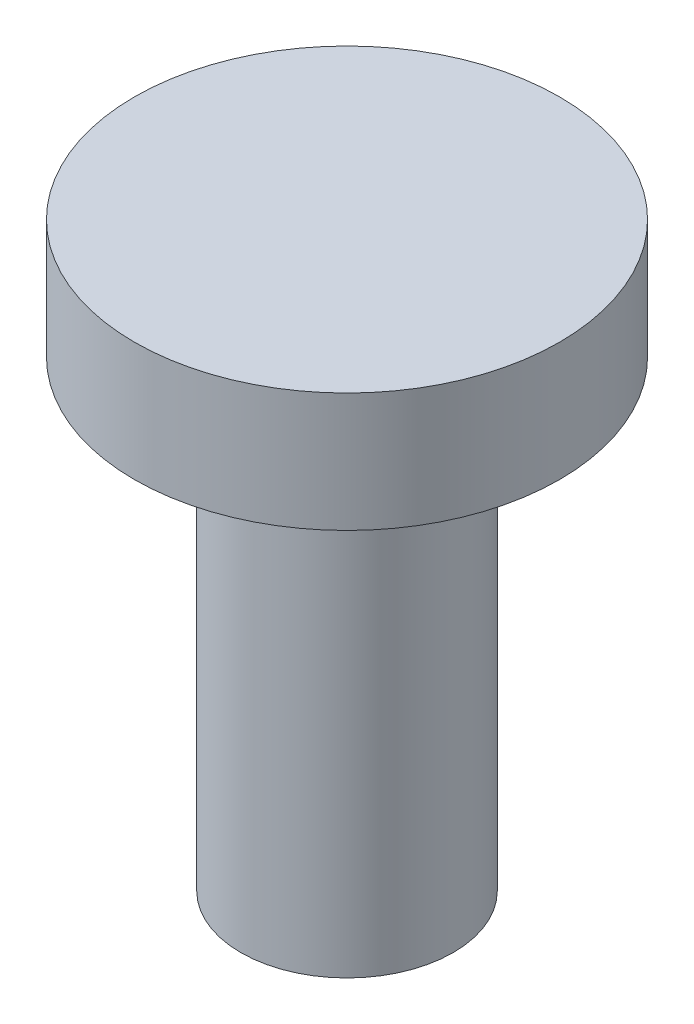
SolidWorks part; units mm, degrees
ref_plane "Front Plane" through (0, 0, 0) normal (0, 0, 1) x (1, 0, 0)
ref_plane "Top Plane" through (0, 0, 0) normal (0, 1, 0) x (1, 0, 0)
ref_plane "Right Plane" through (0, 0, 0) normal (1, 0, 0) x (0, 0, -1)
sketch "Sketch1" plane through (0, 0, 0) normal (0, 1, 0) x (1, 0, 0)
  circle A0 centre (0, 0) radius 5
  circle A2 centre (0, 0) radius 2.5
extrude "Boss-Extrude2" add sketch "Sketch1" along normal blind 3
sketch "Sketch5" plane through (0, 0, 0) normal (0, -1, 0) x (1, 0, 0)
  circle A0 centre (0, 0) radius 2.5
extrude "Boss-Extrude3" add sketch "Sketch5" along normal blind 10.8858 and the other way blind 3
sketch "Sketch6" plane through (0, 3, 0) normal (0, 1, 0) x (1, 0, 0)
  circle A0 centre (0, 0) radius 5
  circle A1 centre (0, 0) radius 5
extrude "Cut-Extrude3" cut sketch "Sketch6" against normal blind 0.2 contours A1
